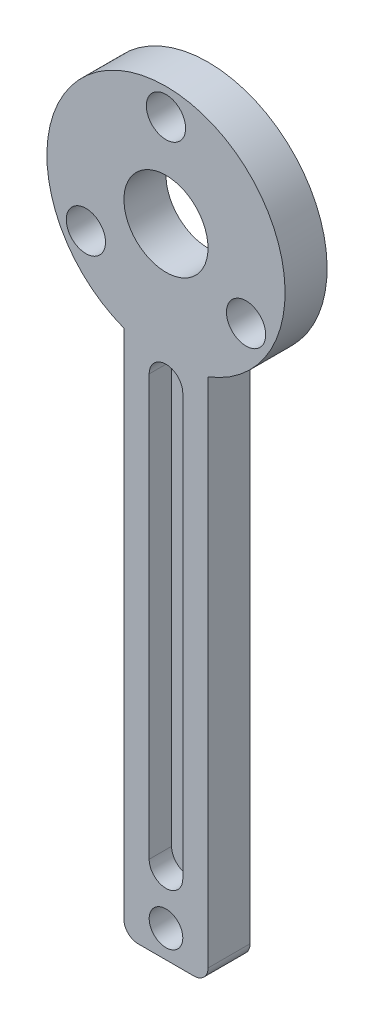
SolidWorks part; units mm, degrees
ref_plane "Front Plane" through (0, 0, 0) normal (0, 0, 1) x (1, 0, 0)
ref_plane "Top Plane" through (0, 0, 0) normal (0, 1, 0) x (1, 0, 0)
ref_plane "Right Plane" through (0, 0, 0) normal (1, 0, 0) x (0, 0, -1)
sketch "Sketch1" plane through (0, 0, 0) normal (0, 1, 0) x (1, 0, 0)
  line L1 (-1.5, -0.75) -> (1.5, -0.75)
  line L2 (-1.5, -0.75) -> (-1.5, 0.75)
  line L3 (-1.5, 0.75) -> (1.5, 0.75)
  line L4 (1.5, -0.75) -> (1.5, 0.75)
  line L5 (-1.5, -0.75) -> (1.5, 0.75) construction
  line L6 (-1.5, 0.75) -> (1.5, -0.75) construction
  dimension "D1" = 3
  dimension "D3" = 1.5
extrude "Boss-Extrude1" add sketch "Sketch1" along normal mid plane 1.5
sketch "Sketch2" plane through (0, 0, 0) normal (0, 0, 1) x (1, 0, 0)
  line L0 (0, 0) -> (0, 22) construction
  line L1 (-1.5, 0) -> (-1.5, 22) construction
  line L2 (1.5, 0) -> (1.5, 22) construction
  line L5 (1.5, 0) -> (1.5, 18.0235)
  line L6 (-1.5, 0) -> (-1.5, 18.0235)
  line L7 (-1.5, 0) -> (1.5, 0)
  arc A2 (1.5, 18.0235) -> (-1.5, 18.0235) centre (0, 22) ccw
  dimension "D2" = 4.25
  dimension "D1" = 22
  dimension "D4" = 1.5
  dimension "D5" = 1.5
extrude "Boss-Extrude2" add sketch "Sketch2" along normal mid plane 1.5
sketch "Sketch4" plane through (0, 0, 0.75) normal (0, 0, 1) x (1, 0, 0)
  circle A0 centre (0, 22) radius 3.3
  circle A1 centre (0, 22) radius 1.5
  arc A2 (1.5, 18.0235) -> (-1.5, 18.0235) centre (0, 22) ccw construction
  circle A3 centre (0, 25.3) radius 0.7
  circle A6 centre (2.8579, 20.35) radius 0.7
  circle A7 centre (-2.8579, 20.35) radius 0.7
  dimension "D1" = 6.6
  dimension "D2" = 3
  dimension "D3" = 1.4
  dimension "D4" = 3
extrude "Cut-Extrude1" cut sketch "Sketch4" against normal through all contours A3 | A7 | A6 | A1
sketch "Sketch5" plane through (0, 0, 0.75) normal (0, 0, 1) x (1, 0, 0)
  line L0 (0, 17.0611) -> (0, 2.0611) construction
  line L1 (0.6, 17.0611) -> (0.6, 2.0611)
  line L2 (-0.6, 17.0611) -> (-0.6, 2.0611)
  line L3 (-1.5, 18.0235) -> (-1.5, -0.75) construction
  line L4 (1.5, -0.75) -> (1.5, 18.0235) construction
  arc A0 (0.6, 17.0611) -> (-0.6, 17.0611) centre (0, 17.0611) ccw
  arc A1 (-0.6, 2.0611) -> (0.6, 2.0611) centre (0, 2.0611) ccw
  point P2 (0, 9.5611)
  dimension "D2" = 0.6
  dimension "D1" = 15
extrude "Cut-Extrude2" cut sketch "Sketch5" against normal blind 0.8
fillet "Fillet1" radius 0.5 2 edges at (1.5, -0.75, 0) (-1.5, -0.75, 0)
sketch "Sketch7" plane through (0, 0, 0) normal (0, 0, 1) x (1, 0, 0)
  line L0 (0, 1.4611) -> (0, -0.75) construction
  line L1 (-1, -0.75) -> (1, -0.75) construction
  arc A1 (-0.6, 2.0611) -> (0.6, 2.0611) centre (0, 2.0611) ccw construction
  circle A2 centre (0, 0.2272) radius 0.6
  dimension "D1" = 1.2
extrude "Cut-Extrude4" cut sketch "Sketch7" against normal mid plane 8
